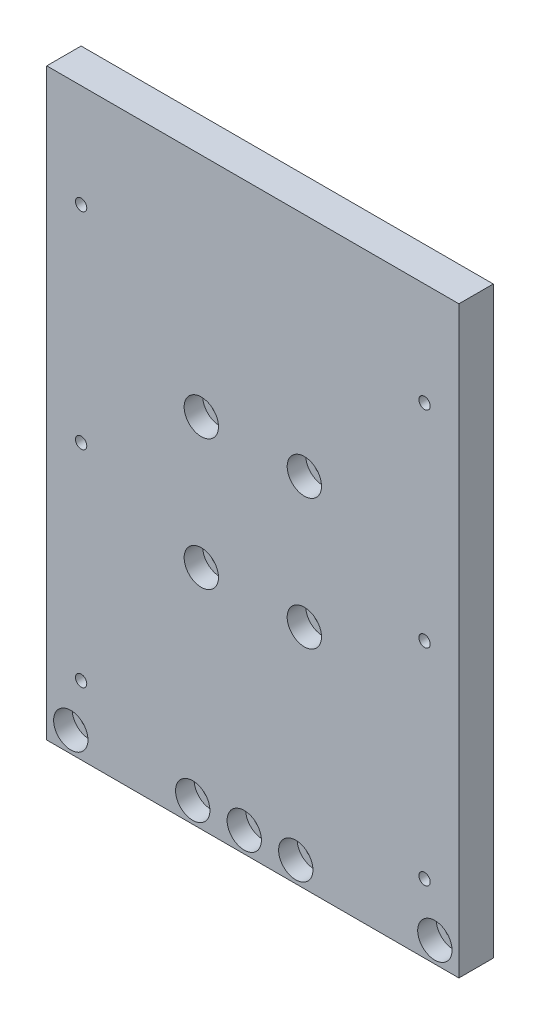
SolidWorks part; units mm, degrees
material "3.3535 (EN-AW 5754)"
ref_plane "Ön Düzlem" through (0, 0, 0) normal (0, 0, 1) x (1, 0, 0)
ref_plane "Üst Düzlem" through (0, 0, 0) normal (0, 1, 0) x (1, 0, 0)
ref_plane "Sağ Düzlem" through (0, 0, 0) normal (1, 0, 0) x (0, 0, -1)
sketch "Sketch1" plane through (0, 0, 0) normal (0, 0, 1) x (1, 0, 0)
  line L1 (60, -85) -> (-60, -85)
  line L2 (60, -85) -> (60, 85)
  line L3 (60, 85) -> (-60, 85)
  line L4 (-60, -85) -> (-60, 85)
  line L5 (60, -85) -> (-60, 85) construction
  line L6 (60, 85) -> (-60, -85) construction
  point P0 (0, 0)
  dimension "D1" = 170
  dimension "D2" = 120
extrude "Boss-Extrude1" add sketch "Sketch1" along normal mid plane 10
hole_wizard "M6 Tapped Hole1" positions "Sketch5" profile "Sketch6" tap size "M6" standard "ISO"
sketch "Sketch5" plane through (0, -85, 0) normal (0, -1, 0) x (-1, 0, 0)
  point P0 (-42.5, -1)
  point P3 (-27.5, -1)
  point P12 (27.5, -1)
  point P15 (42.5, -1)
  point P16 (-42.5, -1)
  point P18 (-27.5, -1)
  point P20 (27.5, -1)
sketch "Sketch6" plane through (42.5, -85, 1) normal (1, 0, 0) x (0, 0, -1)
  line L0 (0, 0) -> (0, 13)
  line L1 (0, 13) -> (2.5, 11.4978)
  line L2 (2.5, 11.4978) -> (2.5, 0)
  line L5 (2.5, 0) -> (0, 0)
  line L10 (0, 13) -> (-2.5, 11.4978) construction
  line L11 (0, -6.35) -> (0, 107.95) construction
  dimension "Tap Drill Dia." = 5
  dimension "Tap Drill Depth" = 13
  dimension "Drill Angle" = 118
cosmetic thread "Hole Thread5" parameters "D1"=10, "D2"=6
cosmetic thread "Hole Thread15" parameters "D1"=10, "D2"=6
cosmetic thread "Hole Thread16" parameters "D1"=10, "D2"=6
cosmetic thread "Hole Thread17" parameters "D1"=10, "D2"=6
hole_wizard "CBORE for M5 Hex Socket Head Cap Screw3" positions "Sketch14" profile "Sketch15" counterbore size "M5" standard "ISO"
sketch "Sketch14" plane through (0, 0, 5) normal (0, 0, 1) x (1, 0, 0)
  line L0 (60, -85) -> (60, 85) construction
  line L1 (-60, 85) -> (-60, -85) construction
  line L2 (-60, -85) -> (60, -85) construction
  point P6 (53, -79)
  point P31 (53, -79)
  point P33 (12.5, -79)
  point P36 (-2.5, -79)
  point P39 (-17.5, -79)
  point P42 (-53, -79)
  dimension "D1" = 7
  dimension "D2" = 7
  dimension "D3" = 6
  dimension "D4" = 15
  dimension "D5" = 15
  dimension "D6" = 35.5
sketch "Sketch15" plane through (53, -79, 5) normal (1, 0, 0) x (0, -1, 0)
  line L0 (0, 0) -> (0, 20)
  line L1 (0, 20) -> (2.75, 20)
  line L2 (2.75, 20) -> (2.75, 5.4)
  line L3 (2.75, 5.4) -> (5, 5.4)
  line L4 (5, 5.4) -> (5, 0)
  line L5 (5, 0) -> (0, 0)
  line L10 (0, 20) -> (-2.75, 20) construction
  line L11 (0, -6.35) -> (0, 107.95) construction
  dimension "Hole Dia." = 5.5
  dimension "Hole Depth" = 20
  dimension "C'Bore Dia." = 10
  dimension "C'Bore Depth" = 5.4
  dimension "Drill Angle" = 180
hole_wizard "CBORE for M4 Hex Socket Head Cap Screw3" positions "Sketch22" profile "Sketch24" counterbore size "M4" standard "ISO"
sketch "Sketch22" plane through (0, 0, -5) normal (0, 0, -1) x (-1, 0, 0)
  line L0 (60, 85) -> (60, -85) construction
  line L1 (-60, 85) -> (60, 85) construction
  point P0 (53, 74.44)
  point P2 (23, 74.44)
  point P4 (23, 36.44)
  point P6 (53, 36.44)
  dimension "D1" = 30
  dimension "D2" = 7
  dimension "D3" = 10.56
  dimension "D4" = 38
sketch "Sketch24" plane through (-53, 74.44, -5) normal (1, 0, 0) x (0, 1, 0)
  line L0 (0, 0) -> (0, 10)
  line L1 (0, 10) -> (2.25, 10)
  line L3 (2.25, 10) -> (2.25, 4.4)
  line L4 (2.25, 4.4) -> (4, 4.4)
  line L5 (4, 4.4) -> (4, 0)
  line L7 (4, 0) -> (0, 0)
  line L11 (0, -6.35) -> (0, 107.95) construction
  dimension "Thru Hole Dia." = 4.5
  dimension "Thru Hole Depth" = 10
  dimension "C'Bore Dia." = 8
  dimension "C'Bore Depth" = 4.4
hole_wizard "CBORE for M4 Hex Socket Head Cap Screw2" positions "Sketch29" profile "Sketch30" counterbore size "M4" standard "ISO"
sketch "Sketch29" plane through (0, 0, -5) normal (0, 0, -1) x (-1, 0, 0)
  line L0 (-60, -85) -> (-60, 85) construction
  line L1 (60, -85) -> (-60, -85) construction
  point P0 (-53, 28.5)
  point P2 (-23, 28.5)
  point P4 (-23, -9.5)
  point P6 (-53, -9.5)
  dimension "D1" = 30
  dimension "D2" = 38
  dimension "D3" = 7
  dimension "D4" = 75.5
sketch "Sketch30" plane through (53, 28.5, -5) normal (1, 0, 0) x (0, 1, 0)
  line L0 (0, 0) -> (0, 13)
  line L1 (0, 13) -> (2.25, 11.6481)
  line L2 (2.25, 11.6481) -> (2.25, 4.4)
  line L3 (2.25, 4.4) -> (4, 4.4)
  line L4 (4, 4.4) -> (4, 0)
  line L5 (4, 0) -> (0, 0)
  line L10 (0, 13) -> (-2.25, 11.6481) construction
  line L11 (0, -6.35) -> (0, 107.95) construction
  dimension "Hole Dia." = 4.5
  dimension "Hole Depth" = 13
  dimension "C'Bore Dia." = 8
  dimension "C'Bore Depth" = 4.4
  dimension "Drill Angle" = 118
hole_wizard "M4 Tapped Hole1" positions "Sketch31" profile "Sketch32" tap size "M4" standard "ISO" end condition through all
sketch "Sketch31" plane through (0, 0, -5) normal (0, 0, -1) x (-1, 0, 0)
  point P0 (50, -65)
  point P3 (50, -5)
  point P6 (50, 55)
  point P9 (-50, 55)
  point P12 (-50, -5)
  point P15 (-50, -65)
sketch "Sketch32" plane through (-50, -65, -5) normal (1, 0, 0) x (0, 1, 0)
  line L0 (0, 0) -> (0, 10)
  line L1 (0, 10) -> (1.65, 10)
  line L2 (1.65, 10) -> (1.65, 0)
  line L5 (1.65, 0) -> (0, 0)
  line L11 (0, -6.35) -> (0, 107.95) construction
  dimension "Thru Tap Drill Dia." = 3.3
  dimension "Thru Tap Drill Depth" = 10
cosmetic thread "Hole Thread24" parameters "D2"=4
cosmetic thread "Hole Thread25" parameters "D2"=4
cosmetic thread "Hole Thread26" parameters "D2"=4
cosmetic thread "Hole Thread27" parameters "D2"=4
cosmetic thread "Hole Thread28" parameters "D2"=4
cosmetic thread "Hole Thread29" parameters "D2"=4
hole_wizard "CBORE for M5 Hex Socket Head Cap Screw2" positions "Sketch33" profile "Sketch34" counterbore size "M5" standard "ISO" end condition through all
sketch "Sketch33" plane through (0, 0, 5) normal (0, 0, 1) x (1, 0, 0)
  point P0 (-15, 19)
  point P2 (15, 19)
  point P4 (15, -19)
  point P6 (-15, -19)
  dimension "D1" = 19
  dimension "D2" = 15
  dimension "D3" = 19
  dimension "D4" = 15
  dimension "D5" = 15
sketch "Sketch34" plane through (-15, 19, 5) normal (1, 0, 0) x (0, -1, 0)
  line L0 (0, 0) -> (0, 10)
  line L1 (0, 10) -> (2.75, 10)
  line L3 (2.75, 10) -> (2.75, 5.4)
  line L4 (2.75, 5.4) -> (5, 5.4)
  line L5 (5, 5.4) -> (5, 0)
  line L7 (5, 0) -> (0, 0)
  line L11 (0, -6.35) -> (0, 107.95) construction
  dimension "Thru Hole Dia." = 5.5
  dimension "Thru Hole Depth" = 10
  dimension "C'Bore Dia." = 10
  dimension "C'Bore Depth" = 5.4
sketch "Sketch35" plane through (0, 0, -5) normal (0, 0, -1) x (-1, 0, 0)
  line L1 (-23, 23.5) -> (23, 23.5)
  line L2 (-31, 15.5) -> (-31, -15.5)
  line L3 (-23, -23.5) -> (23, -23.5)
  line L4 (31, 15.5) -> (31, -15.5)
  line L5 (-31, 23.5) -> (31, -23.5) construction
  line L6 (-31, -23.5) -> (31, 23.5) construction
  arc A0 (-31, -15.5) -> (-23, -23.5) centre (-23, -15.5) ccw
  arc A1 (23, -23.5) -> (31, -15.5) centre (23, -15.5) ccw
  arc A2 (23, 23.5) -> (31, 15.5) centre (23, 15.5) cw
  arc A3 (-23, 23.5) -> (-31, 15.5) centre (-23, 15.5) ccw
  point P0 (0, 0)
  dimension "D3" = 8
  dimension "D1" = 47
  dimension "D2" = 62
extrude "Cut-Extrude1" cut sketch "Sketch35" against normal blind 3
